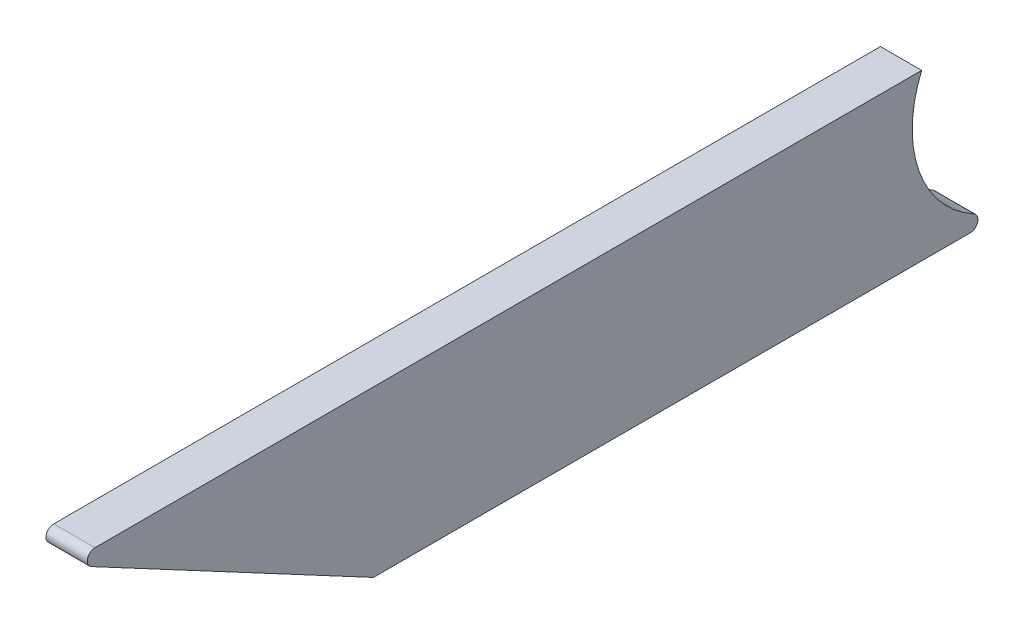
SolidWorks part; units mm, degrees
material "Q355"
ref_plane "前视基准面" through (0, 0, 0) normal (0, 0, 1) x (1, 0, 0)
ref_plane "上视基准面" through (0, 0, 0) normal (0, 1, 0) x (1, 0, 0)
ref_plane "右视基准面" through (0, 0, 0) normal (1, 0, 0) x (0, 0, -1)
sketch "草图1" plane through (0, 0, 0) normal (1, 0, 0) x (0, 0, -1)
  line L12 (-375, 18) -> (-42.332, 18)
  line L17 (-375, 18) -> (-255, -46)
  line L19 (0, -46) -> (-255, -46)
  arc A0 (-42.332, 18) -> (0, -46) centre (0, 0) ccw
  dimension "D2" = 255
  dimension "D3" = 120
  dimension "D4" = 64
  dimension "D16" = 46
extrude "凸台-拉伸1" add sketch "草图1" along normal blind 16
fillet "圆角1" radius 3 2 edges at (8, -46, 0) (8, 18, 375)
